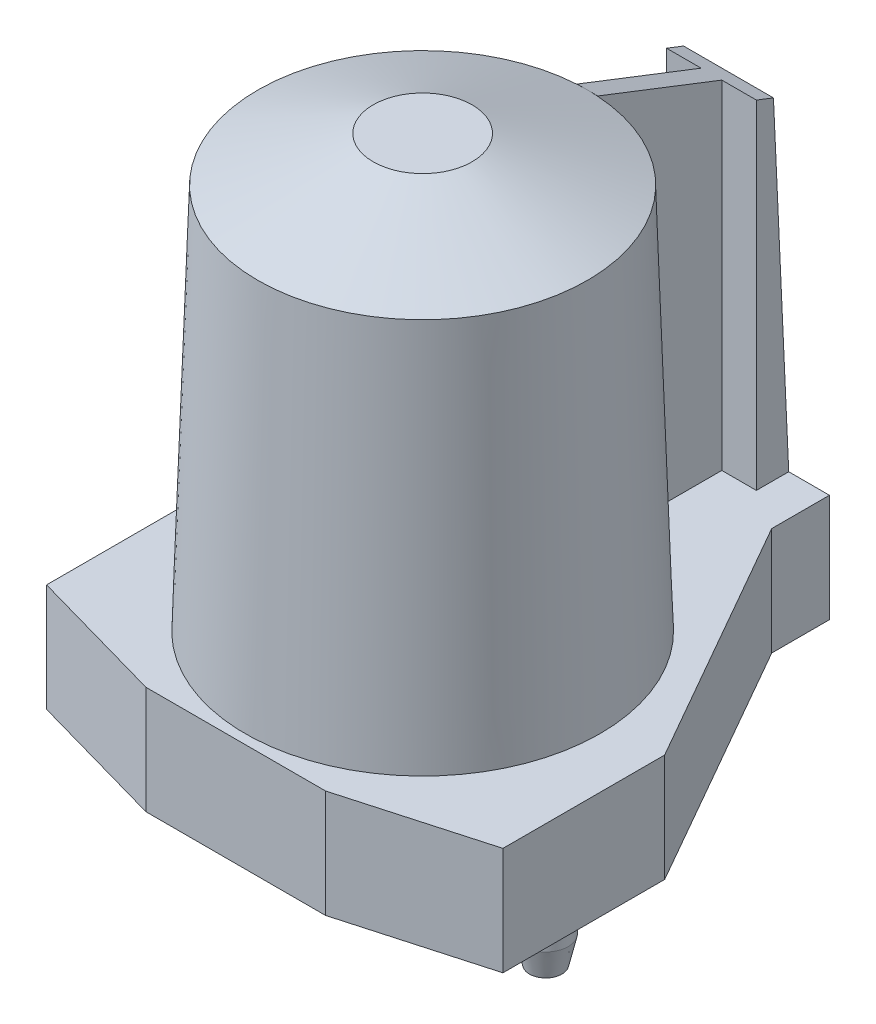
SolidWorks part; units mm, degrees
ref_plane "Plan de face" through (0, 0, 0) normal (0, 0, 1) x (1, 0, 0)
ref_plane "Plan de dessus" through (0, 0, 0) normal (0, 1, 0) x (1, 0, 0)
ref_plane "Plan de droite" through (0, 0, 0) normal (1, 0, 0) x (0, 0, -1)
sketch "Esquisse1" plane through (0, 0, 0) normal (0, 1, 0) x (1, 0, 0)
  line L0 (5, -10.4) -> (-5, -10.4)
  line L1 (-5, -10.4) -> (-12.7, -8.2297)
  line L2 (-12.7, -8.2297) -> (-12.7, 0.7703)
  line L5 (-4.765, 17.6) -> (4.765, 17.6)
  line L6 (0, 17.6) -> (0, -10.4) construction
  line L9 (12.7, -8.2297) -> (12.7, 0.7703)
  line L10 (5, -10.4) -> (12.7, -8.2297)
  line L11 (-12.7, 0.7703) -> (-4.765, 14.664)
  line L12 (-4.765, 14.664) -> (-4.765, 17.6)
  line L13 (12.7, 0.7703) -> (4.765, 14.664)
  line L14 (4.765, 14.664) -> (4.765, 17.6)
  dimension "D1" = 5
  dimension "D2" = 8
  dimension "D3" = 12.7
  dimension "D4" = 10.4
  dimension "D5" = 4.765
  dimension "D6" = 9
  dimension "D7" = 28
  dimension "D8" = 16
extrude "Boss.-Extru.1" add sketch "Esquisse1" along normal blind 6
sketch "Esquisse2" plane through (0, 0, 0) normal (1, 0, 0) x (0, 0, -1)
  line L0 (0, 6) -> (-9.875, 6)
  line L1 (-9.875, 6) -> (-9.175, 27.5)
  line L2 (-9.175, 27.5) -> (-2.75, 30)
  line L3 (-2.75, 30) -> (0, 30)
  line L4 (0, 30) -> (0, 6)
  line L5 (0, 0) -> (0, 6) construction
  line L6 (-9.175, 27.5) -> (0, 27.5) construction
  line L7 (-8.2297, 6) -> (0.7703, 6) construction
  dimension "D1" = 9.875
  dimension "D2" = 9.175
  dimension "D3" = 2.75
  dimension "D4" = 2.5
  dimension "D5" = 21.5
revolve "Révolution1" add sketch "Esquisse2" angle 360 about L4
sketch "Esquisse3" plane through (0, 0, 0) normal (1, 0, 0) x (0, 0, -1)
  line L0 (9.175, 27.5) -> (17.0244, 24.4457)
  line L1 (17.0244, 24.4457) -> (17.875, 6)
  line L3 (17.875, 6) -> (9.875, 6)
  line L4 (9.875, 6) -> (9.175, 27.5) construction
  line L5 (9.175, 27.5) -> (2.75, 30) construction
  line L6 (17.0244, 24.4457) -> (9.2744, 24.4457) construction
  line L7 (9.875, 6) -> (8.375, 6)
  line L8 (8.375, 6) -> (8.375, 27.5)
  line L9 (8.375, 27.5) -> (9.175, 27.5)
  dimension "D1" = 7.75
  dimension "D2" = 8
  dimension "D3" = 0.8
extrude "Boss.-Extru.5" add sketch "Esquisse3" along normal mid plane 1.15
sketch "Esquisse4" plane through (0, 0, 0) normal (1, 0, 0) x (0, 0, -1)
  line L0 (17.6, 0) -> (17.6, 6)
  line L1 (17.6, 6) -> (17.875, 6)
  line L2 (17.875, 6) -> (17.875, 0)
  line L3 (17.875, 0) -> (17.6, 0)
extrude "Boss.-Extru.6" add sketch "Esquisse4" along normal up to surface and the other way up to surface up to face at (4.765, 3, -16.132) other way up to face at (-4.765, 3, -16.132)
sketch "Esquisse5" plane through (0, 0, 0) normal (1, 0, 0) x (0, 0, -1)
  line L0 (16.0744, 24.8154) -> (17.0244, 24.4457)
  line L1 (17.0244, 24.4457) -> (17.875, 6)
  line L2 (17.875, 6) -> (16.0744, 6)
  line L5 (16.0744, 6) -> (16.0744, 24.8154)
  line L6 (17.875, 6) -> (17.0244, 24.4457) construction
  line L7 (17.0244, 24.4457) -> (9.175, 27.5) construction
  line L8 (9.8582, 6) -> (17.875, 6) construction
  dimension "D1" = 0.95
extrude "Boss.-Extru.7" add sketch "Esquisse5" along normal mid plane 5
sketch "Esquisse6" plane through (0, 0, 0) normal (0, -1, 0) x (1, 0, 0)
  line L0 (0, 0) -> (0, 10.4) construction
  line L1 (-5, 10.4) -> (5, 10.4) construction
  circle A0 centre (-11, 4.15) radius 1.25
  circle A1 centre (11, 4.15) radius 1.25
  dimension "D2" = 2.5
  dimension "D1" = 11
  dimension "D3" = 6.25
extrude "Boss.-Extru.8" add sketch "Esquisse6" along normal blind 2.5
chamfer "Chanfrein1" distance 1.5 angle 13 2 edges at (11, -2.5, 5.4) (-11, -2.5, 2.9)
